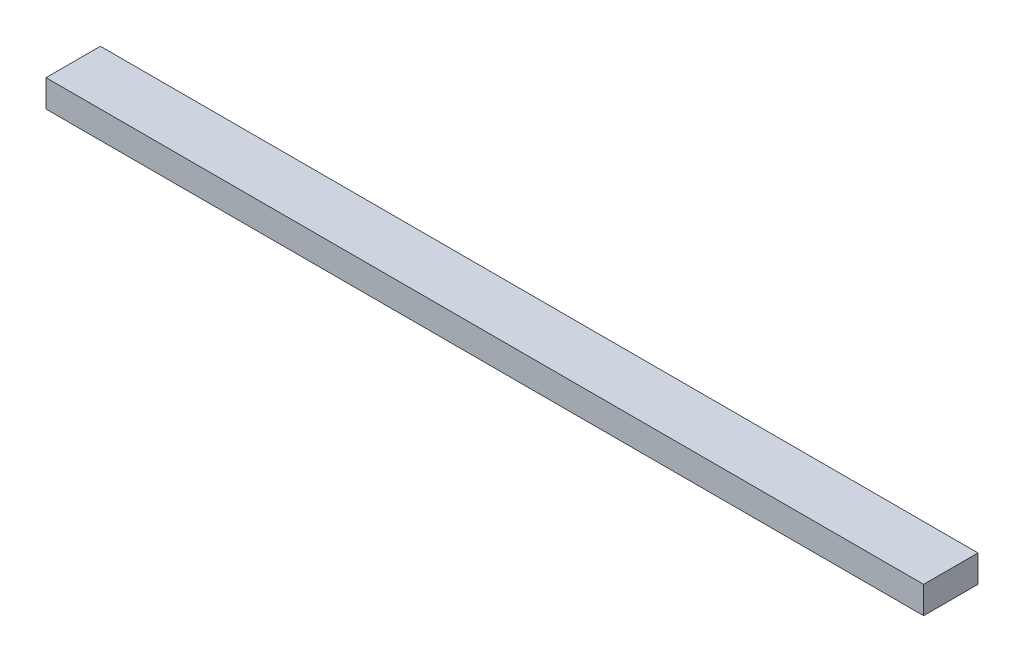
SolidWorks part; units mm, degrees
ref_plane "Plan de face" through (0, 0, 0) normal (0, 0, 1) x (1, 0, 0)
ref_plane "Plan de dessus" through (0, 0, 0) normal (0, 1, 0) x (1, 0, 0)
ref_plane "Plan de droite" through (0, 0, 0) normal (1, 0, 0) x (0, 0, -1)
sketch "Esquisse1" plane through (0, 0, 0) normal (0, 0, 1) x (1, 0, 0)
  line L1 (-355, -22) -> (355, -22)
  line L2 (-355, -22) -> (-355, 0)
  line L3 (-355, 0) -> (355, 0)
  line L4 (355, -22) -> (355, 0)
  dimension "D1" = 710
  dimension "D2" = 22
extrude "Boss.-Extru.1" add sketch "Esquisse1" along normal blind 44 contours L3 L4 L1 L2
